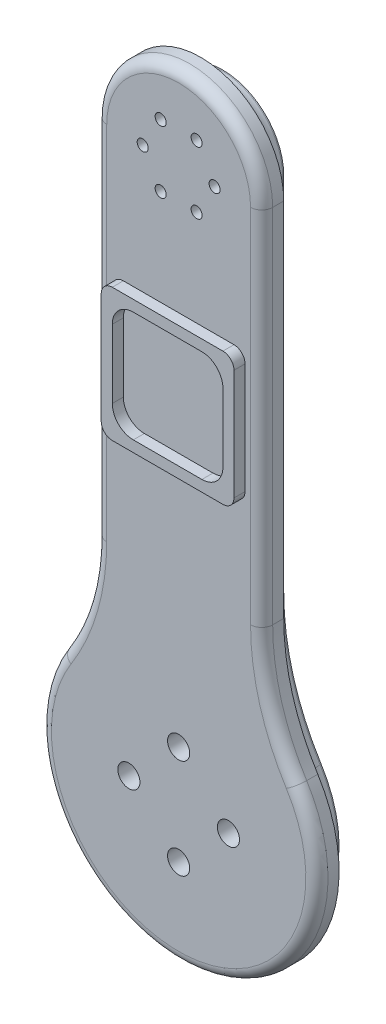
SolidWorks part; units mm, degrees
ref_plane "Front Plane" through (0, 0, 0) normal (0, 0, 1) x (1, 0, 0)
ref_plane "Top Plane" through (0, 0, 0) normal (0, 1, 0) x (1, 0, 0)
ref_plane "Right Plane" through (0, 0, 0) normal (1, 0, 0) x (0, 0, -1)
sketch "Sketch1" plane through (0, 0, 0) normal (0, 0, 1) x (1, 0, 0)
  line L0 (0, 0) -> (0, 500) construction
  line L1 (-75, 500) -> (-75, 173.2051)
  line L2 (75, 500) -> (75, 173.2051)
  arc A0 (75, 500) -> (-75, 500) centre (0, 500) ccw
  arc A1 (-105.7692, 66.6173) -> (105.7692, 66.6173) centre (0, 0) ccw
  arc A2 (-75, 173.2051) -> (-105.7692, 66.6173) centre (-275, 173.2051) cw
  arc A3 (75, 173.2051) -> (105.7692, 66.6173) centre (275, 173.2051) ccw
  dimension "D2" = 150
  dimension "D3" = 250
  dimension "D4" = 200
  dimension "D1" = 500
extrude "Boss-Extrude1" add sketch "Sketch1" along normal blind 20
sketch "Sketch2" plane through (0, 0, 0) normal (0, 0, -1) x (-1, 0, 0)
  line L4 (-55, 500) -> (-55, 173.2051)
  line L5 (55, 173.2051) -> (55, 500)
  line L6 (-55, 500) -> (-55, 173.2051)
  line L7 (55, 173.2051) -> (55, 500)
  arc A8 (55, 500) -> (-55, 500) centre (0, 500) ccw
  arc A9 (-88.8462, 55.9586) -> (-55, 173.2051) centre (-275, 173.2051) ccw
  arc A10 (-88.8462, 55.9586) -> (88.8462, 55.9586) centre (0, 0) ccw
  arc A11 (55, 173.2051) -> (88.8462, 55.9586) centre (275, 173.2051) ccw
  arc A12 (55, 500) -> (-55, 500) centre (0, 500) ccw
  arc A13 (-88.8462, 55.9586) -> (-55, 173.2051) centre (-275, 173.2051) ccw
  arc A14 (-88.8462, 55.9586) -> (88.8462, 55.9586) centre (0, 0) ccw
  arc A15 (55, 173.2051) -> (88.8462, 55.9586) centre (275, 173.2051) ccw
  dimension "D1" = 20
extrude "Boss-Extrude2" add sketch "Sketch2" along normal blind 20
fillet "Fillet1" radius 19 6 edges at (0, 555, 0) (-55, 336.6025, 0) (-63.6308, 112.1881, 0) (0, -105, 0) (63.6308, 112.1881, 0) (55, 336.6025, 0)
fillet "Fillet2" radius 10 6 edges at (75, 336.6025, 20) (82.8462, 117.7351, 20) (0, -125, 20) (-82.8462, 117.7351, 20) (-75, 336.6025, 20) (0, 575, 20)
sketch "Sketch3" plane through (0, 0, 20) normal (0, 0, 1) x (1, 0, 0)
  circle A0 centre (0, 500) radius 32.5 construction
  circle A1 centre (-32.5, 500) radius 5
  circle A2 centre (-16.25, 528.1458) radius 5
  circle A3 centre (16.25, 528.1458) radius 5
  circle A4 centre (32.5, 500) radius 5
  circle A5 centre (16.25, 471.8542) radius 5
  circle A6 centre (-16.25, 471.8542) radius 5
  circle A7 centre (0, 0) radius 45 construction
  circle A8 centre (-45, 0) radius 10
  circle A9 centre (0, 45) radius 10
  circle A10 centre (45, 0) radius 10
  circle A11 centre (0, -45) radius 10
  point P18 (0, 500)
  point P30 (0, 0)
  dimension "D1" = 65
  dimension "D2" = 10
  dimension "D4" = 20
  dimension "D5" = 90
  dimension "D3" = 6
  dimension "D6" = 4
extrude "Cut-Extrude1" cut sketch "Sketch3" against normal through all
sketch "Sketch4" plane through (0, 0, 20) normal (0, 0, 1) x (1, 0, 0)
  line L0 (0, 565) -> (0, 325) construction
  line L1 (-50, 385) -> (50, 385) construction
  line L2 (-60, 265) -> (60, 265)
  line L3 (-60, 265) -> (-60, 385)
  line L4 (-60, 385) -> (60, 385)
  line L5 (60, 265) -> (60, 385)
  line L6 (-60, 265) -> (60, 385) construction
  line L7 (-60, 385) -> (60, 265) construction
  arc A0 (65, 500) -> (-65, 500) centre (0, 500) ccw construction
  point P11 (0, 0)
  dimension "D2" = 120
  dimension "D3" = 120
extrude "Boss-Extrude3" add sketch "Sketch4" along normal blind 10
fillet "Fillet3" radius 10 4 edges at (-60, 265, 25) (60, 265, 25) (-60, 385, 25) (60, 385, 25)
sketch "Sketch5" plane through (0, 0, 30) normal (0, 0, 1) x (1, 0, 0)
  line L0 (31, 275) -> (-31, 275) construction
  line L1 (50, 356) -> (50, 294) construction
  line L2 (-31, 375) -> (31, 375) construction
  line L3 (-50, 294) -> (-50, 356) construction
  line L4 (31, 275) -> (-31, 275)
  line L5 (50, 356) -> (50, 294)
  line L6 (-31, 375) -> (31, 375)
  line L7 (-50, 294) -> (-50, 356)
  arc A0 (31, 275) -> (50, 294) centre (31, 294) ccw construction
  arc A1 (50, 356) -> (31, 375) centre (31, 356) ccw construction
  arc A2 (-31, 375) -> (-50, 356) centre (-31, 356) ccw construction
  arc A3 (-50, 294) -> (-31, 275) centre (-31, 294) ccw construction
  arc A4 (31, 275) -> (50, 294) centre (31, 294) ccw
  arc A5 (50, 356) -> (31, 375) centre (31, 356) ccw
  arc A6 (-31, 375) -> (-50, 356) centre (-31, 356) ccw
  arc A7 (-50, 294) -> (-31, 275) centre (-31, 294) ccw
extrude "Cut-Extrude2" cut sketch "Sketch5" against normal up to surface (10 mm away) up to face at (10, -45, 20)
